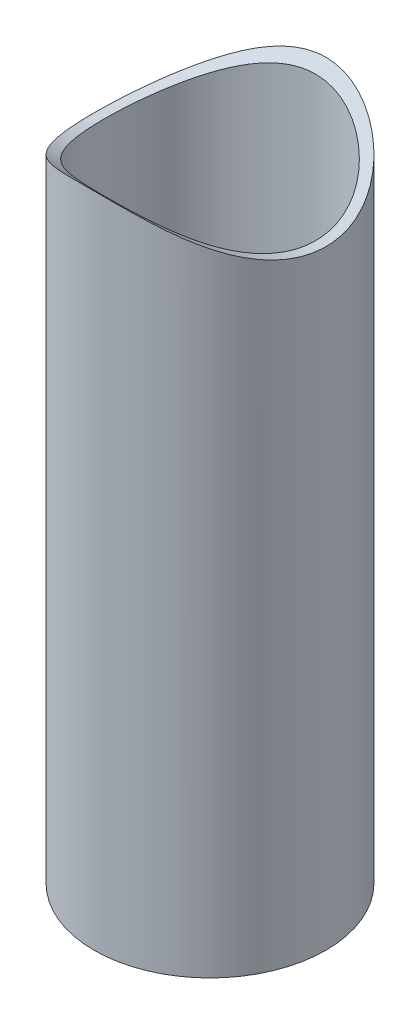
SolidWorks part; units mm, degrees
ref_plane "Front Plane" through (0, 0, 0) normal (0, 0, 1) x (1, 0, 0)
ref_plane "Top Plane" through (0, 0, 0) normal (0, 1, 0) x (1, 0, 0)
ref_plane "Right Plane" through (0, 0, 0) normal (1, 0, 0) x (0, 0, -1)
sketch "Sketch1" plane through (0, 0, 0) normal (0, 1, 0) x (1, 0, 0)
  circle A0 centre (0, 0) radius 10.25
  circle A1 centre (0, 0) radius 11.25
  dimension "D1" = 1
  dimension "D2" = 20.5
extrude "Boss-Extrude1" add sketch "Sketch1" along normal blind 75
sketch "Sketch2" plane through (0, 0, 0) normal (0, 0, 1) x (1, 0, 0)
  line L0 (0, 0) -> (0, 75) construction
  line L1 (-11.25, 0) -> (11.25, 0) construction
  line L2 (0, 75) -> (-75.4581, 75) construction
  line L3 (-75.4581, 75) -> (31.1477, 75)
  dimension "D1" = 75
  dimension "D2" = 0
ref_plane "Plane1" through (31.1477, 75, 0) normal (1, 0, 0) x (0, -1, 0)
sketch "Sketch3" plane through (31.1477, 75, 0) normal (1, 0, 0) x (0, -1, 0)
  circle A0 centre (0, 0) radius 15.875
  point P2 (8.718, 0.8251)
  point P4 (-0.028, 0)
  dimension "D1" = 31.75
sweep "Cut-Sweep1" cut profiles "Sketch3" path "Sketch2"
